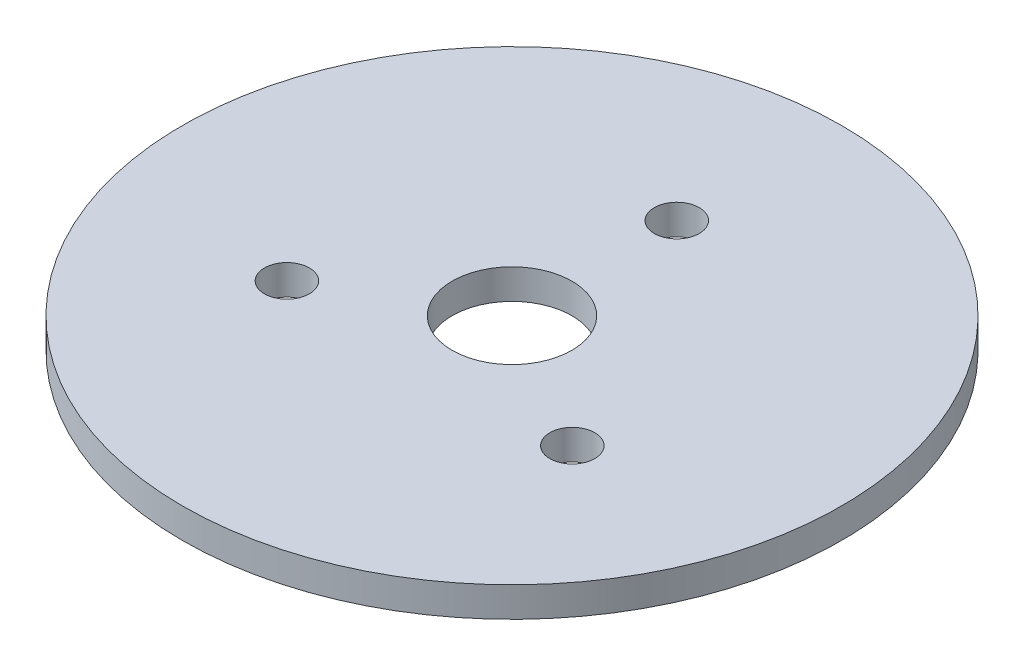
SolidWorks part; units mm, degrees
ref_plane "Front Plane" through (0, 0, 0) normal (0, 0, 1) x (1, 0, 0)
ref_plane "Top Plane" through (0, 0, 0) normal (0, 1, 0) x (1, 0, 0)
ref_plane "Right Plane" through (0, 0, 0) normal (1, 0, 0) x (0, 0, -1)
sketch "Sketch1" plane through (0, 0, 0) normal (0, 1, 0) x (1, 0, 0)
  circle A0 centre (0, 0) radius 22
  circle A1 centre (0, 0) radius 4
  circle A2 centre (0, 11) radius 1.5
  circle A3 centre (9.5263, -5.5) radius 1.5
  circle A4 centre (-9.5263, -5.5) radius 1.5
  point P13 (0, 0)
  dimension "D1" = 44
  dimension "D2" = 8
  dimension "D3" = 3
  dimension "D4" = 11
  dimension "D5" = 3
extrude "Boss-Extrude1" add sketch "Sketch1" along normal blind 2
